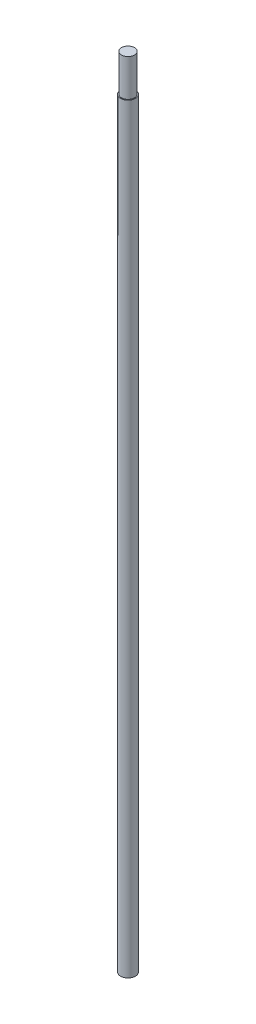
SolidWorks part; units mm, degrees
ref_plane "Plan de face" through (0, 0, 0) normal (0, 0, 1) x (1, 0, 0)
ref_plane "Plan de dessus" through (0, 0, 0) normal (0, 1, 0) x (1, 0, 0)
ref_plane "Plan de droite" through (0, 0, 0) normal (1, 0, 0) x (0, 0, -1)
sketch "Esquisse1" plane through (0, 0, 0) normal (0, 1, 0) x (1, 0, 0)
  circle A0 centre (0, 0) radius 4
  dimension "D1" = 8
extrude "Boss.-Extru.1" add sketch "Esquisse1" along normal blind 410
sketch "Esquisse2" plane through (0, 410, 0) normal (0, 1, 0) x (1, 0, 0)
  circle A0 centre (0, 0) radius 3.5
  dimension "D1" = 7
extrude "Boss.-Extru.2" add sketch "Esquisse2" along normal blind 20
